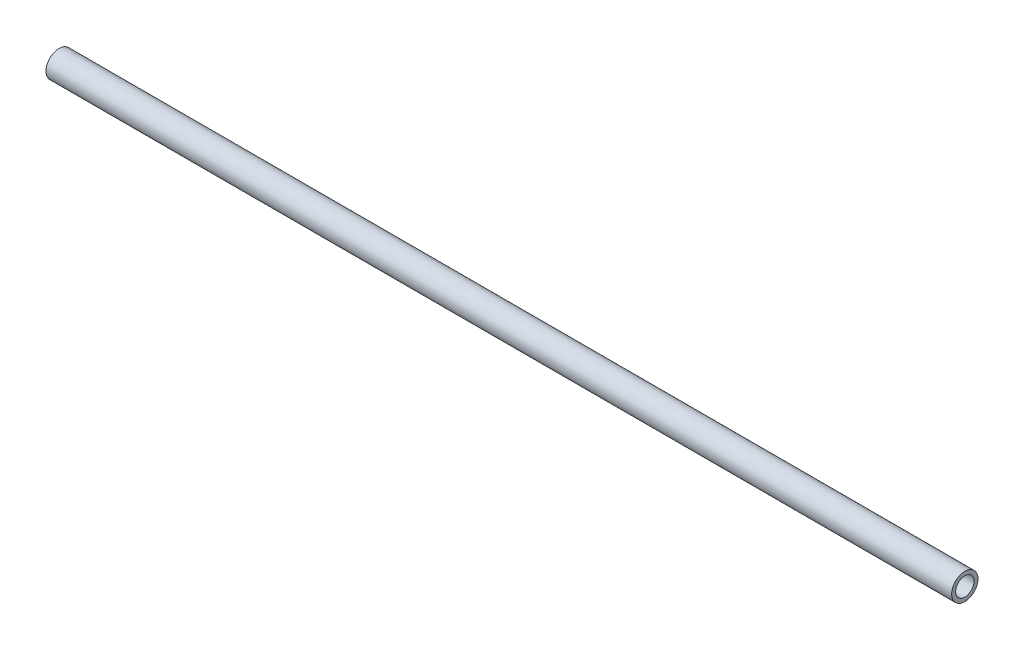
SolidWorks part; units mm, degrees
material "6061-T6 (SS)"
ref_plane "Front Plane" through (0, 0, 0) normal (0, 0, 1) x (1, 0, 0)
ref_plane "Top Plane" through (0, 0, 0) normal (0, 1, 0) x (1, 0, 0)
ref_plane "Right Plane" through (0, 0, 0) normal (1, 0, 0) x (0, 0, -1)
sketch "Sketch1" plane through (0, 0, 0) normal (1, 0, 0) x (0, 0, -1)
  circle A0 centre (0, 0) radius 15.875
  circle A1 centre (0, 0) radius 11.1125
  dimension "D1" = 31.75
  dimension "D2" = 4.7625
extrude "Boss-Extrude1" add sketch "Sketch1" along normal blind 1092.2
